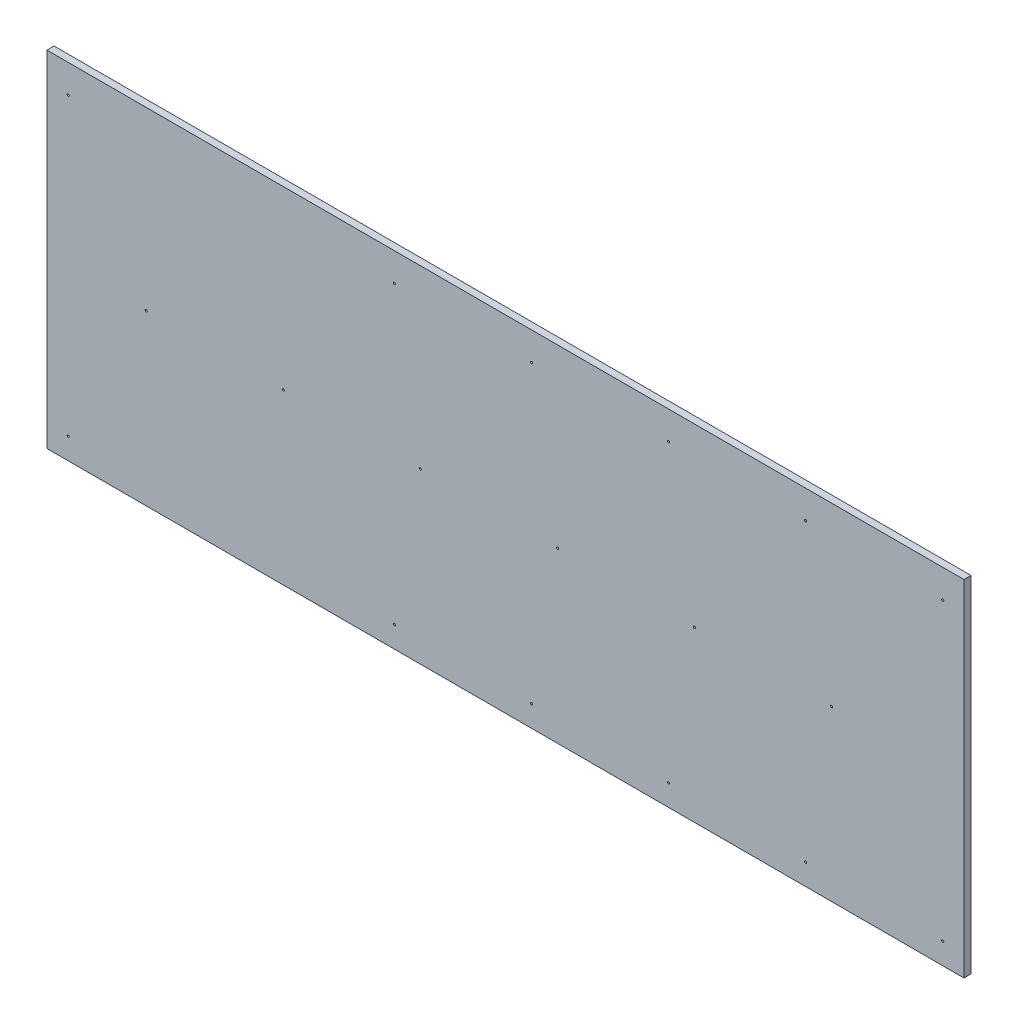
SolidWorks part; units mm, degrees
ref_plane "Front Plane" through (0, 0, 0) normal (0, 0, 1) x (1, 0, 0)
ref_plane "Top Plane" through (0, 0, 0) normal (0, 1, 0) x (1, 0, 0)
ref_plane "Right Plane" through (0, 0, 0) normal (1, 0, 0) x (0, 0, -1)
sketch "Sketch1" plane through (0, 0, 0) normal (0, 0, 1) x (1, 0, 0)
  line L1 (388, -146) -> (-388, -146)
  line L2 (388, -146) -> (388, 146)
  line L3 (388, 146) -> (-388, 146)
  line L4 (-388, -146) -> (-388, 146)
  line L5 (388, -146) -> (-388, 146) construction
  line L6 (388, 146) -> (-388, -146) construction
  point P0 (0, 0)
  dimension "D1" = 776
  dimension "D2" = 292
extrude "Boss-Extrude1" add sketch "Sketch1" along normal blind 6
sketch "Sketch2" plane through (0, 0, 0) normal (0, 0, -1) x (-1, 0, 0)
  circle A0 centre (-370, -128) radius 0.9
  circle A1 centre (-370, 122) radius 0.9
  circle A2 centre (370, -128) radius 0.9
  circle A3 centre (370, 122) radius 0.9
  circle A4 centre (-276, -3) radius 0.9
  circle A5 centre (-254, -128) radius 0.9
  circle A6 centre (-254, 122) radius 0.9
  circle A7 centre (-160, -3) radius 0.9
  circle A8 centre (-138, -128) radius 0.9
  circle A9 centre (-138, 122) radius 0.9
  circle A10 centre (-44, -3) radius 0.9
  circle A11 centre (-22, -128) radius 0.9
  circle A12 centre (-22, 122) radius 0.9
  circle A13 centre (72, -3) radius 0.9
  circle A14 centre (94, -128) radius 0.9
  circle A15 centre (94, 122) radius 0.9
  circle A16 centre (188, -3) radius 0.9
  circle A17 centre (304, -3) radius 0.9
  dimension "D1" = 1.8
extrude "Cut-Extrude1" cut sketch "Sketch2" against normal blind 6
